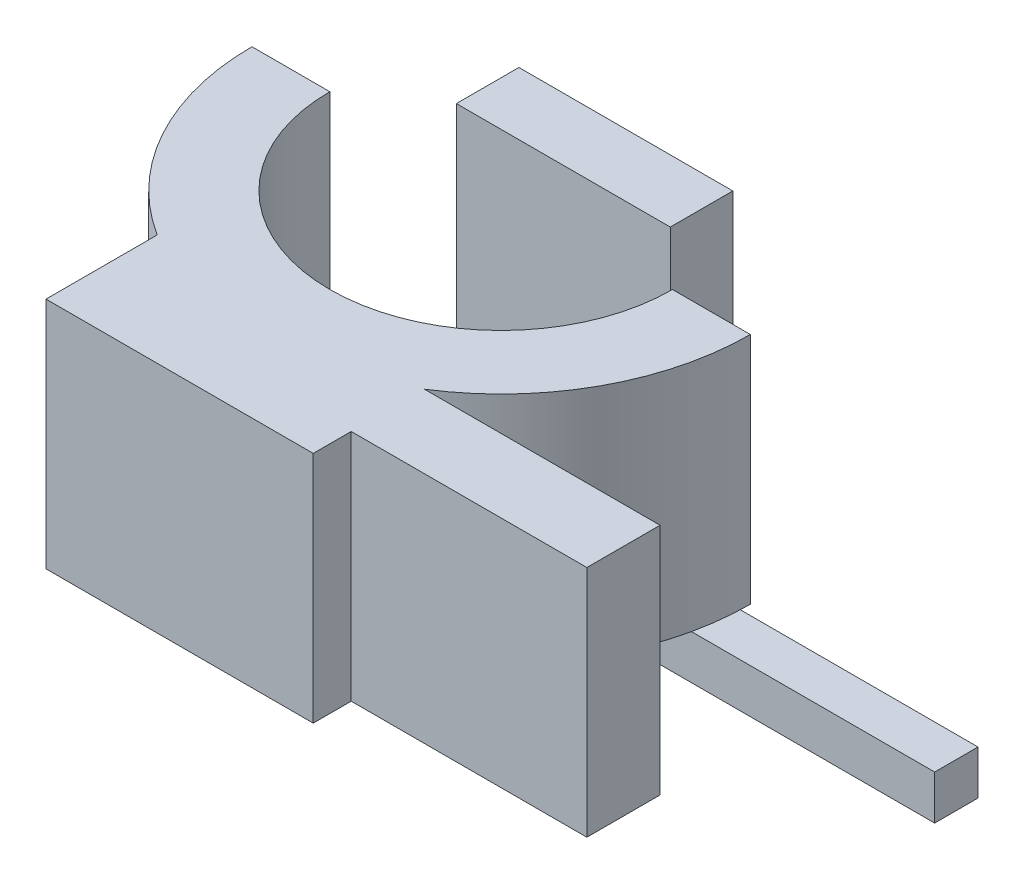
SolidWorks part; units mm, degrees
ref_plane "Front Plane" through (0, 0, 0) normal (0, 0, 1) x (1, 0, 0)
ref_plane "Top Plane" through (0, 0, 0) normal (0, 1, 0) x (1, 0, 0)
ref_plane "Right Plane" through (0, 0, 0) normal (1, 0, 0) x (0, 0, -1)
sketch "Sketch3" plane through (0, 0, 0) normal (0, 1, 0) x (1, 0, 0)
  line L0 (-32, 0) -> (-22, 0)
  line L1 (22, 0) -> (32, 0)
  line L2 (-12.5555, 6.8065) -> (-12.5555, 14.8362)
  line L4 (-17.1578, -27.0113) -> (-17.1578, -33.1142)
  line L5 (-17.1578, -33.1142) -> (4.4387, -33.1142)
  line L11 (-12.5555, 14.8362) -> (14.9101, 14.8362)
  line L12 (14.9101, 14.8362) -> (14.9101, 6.8065)
  line L13 (14.9101, 6.8065) -> (-12.5555, 6.8065)
  line L14 (4.4387, -33.1142) -> (17.1578, -33.1142)
  line L15 (17.1578, -33.1142) -> (17.1578, -27.0113)
  arc A0 (-32, 0) -> (-17.1578, -27.0113) centre (0, 0) ccw
  arc A1 (-22, 0) -> (22, 0) centre (0, 0) ccw
  arc A2 (17.1578, -27.0113) -> (32, 0) centre (0, 0) ccw
  dimension "D1" = 32
  dimension "D5" = 22
extrude "Boss-Extrude1" add sketch "Sketch3" along normal blind 25.4
sketch "Sketch6" plane through (0, 25.4, 0) normal (0, 1, 0) x (1, 0, 0)
  line L1 (17.1578, -27.0113) -> (37.1578, -27.0113)
  line L2 (17.1578, -33.1142) -> (17.1578, -27.0113) construction
  line L6 (-17.1578, -41.2897) -> (17.1578, -41.2897)
  line L7 (-17.1578, -33.1142) -> (-17.1578, -41.2897)
  line L8 (37.1578, -27.0113) -> (47.4163, -27.0113)
  line L9 (47.4163, -27.0113) -> (47.4163, -33.1142)
  line L10 (47.4163, -33.1142) -> (47.4163, -36.4107)
  line L11 (47.4163, -36.4107) -> (17.1578, -36.4107)
  line L12 (17.1578, -36.4107) -> (17.1578, -41.2897)
  line L15 (-17.1578, -27.0113) -> (-17.1578, -33.1142)
  line L16 (-17.1578, -33.1142) -> (17.1578, -33.1142)
  line L17 (17.1578, -33.1142) -> (17.1578, -27.0113)
  line L18 (32, 0) -> (22, 0)
  line L19 (-22, 0) -> (-32, 0)
  line L20 (-17.1578, -27.0113) -> (-17.1578, -33.1142)
  line L23 (32, 0) -> (22, 0)
  line L24 (-22, 0) -> (-32, 0)
  arc A3 (-32, 0) -> (-17.1578, -27.0113) centre (0, 0) ccw
  arc A4 (17.1578, -27.0113) -> (32, 0) centre (0, 0) ccw
  arc A5 (-22, 0) -> (22, 0) centre (0, 0) ccw
  arc A6 (-32, 0) -> (-17.1578, -27.0113) centre (0, 0) ccw
  arc A7 (17.1578, -27.0113) -> (32, 0) centre (0, 0) ccw
  arc A8 (-22, 0) -> (22, 0) centre (0, 0) ccw
  dimension "D2" = 30.2586
  dimension "D3" = 0
extrude "Boss-Extrude3" add sketch "Sketch6" against normal blind 30
sketch "Sketch11" plane through (0, 0, 0) normal (0, -1, 0) x (-1, 0, 0)
  line L1 (-2.7735, 13.4602) -> (2.0417, 13.4602)
  line L2 (-2.7735, 13.4602) -> (-2.7735, 7.8929)
  line L3 (-2.7735, 7.8929) -> (2.0417, 7.8929)
  line L4 (2.0417, 13.4602) -> (2.0417, 7.8929)
extrude "Boss-Extrude7" add sketch "Sketch11" along normal blind 25
sketch "Sketch12" plane through (2.7735, 0, 0) normal (1, 0, 0) x (0, 0, -1)
  line L0 (7.8929, -25) -> (7.8929, 0) construction
  line L1 (7.8929, -19.3172) -> (13.4602, -19.3172)
  line L2 (7.8929, -19.3172) -> (7.8929, -25)
  line L3 (7.8929, -25) -> (13.4602, -25)
  line L4 (13.4602, -19.3172) -> (13.4602, -25)
extrude "Boss-Extrude10" add sketch "Sketch12" along normal blind 45
